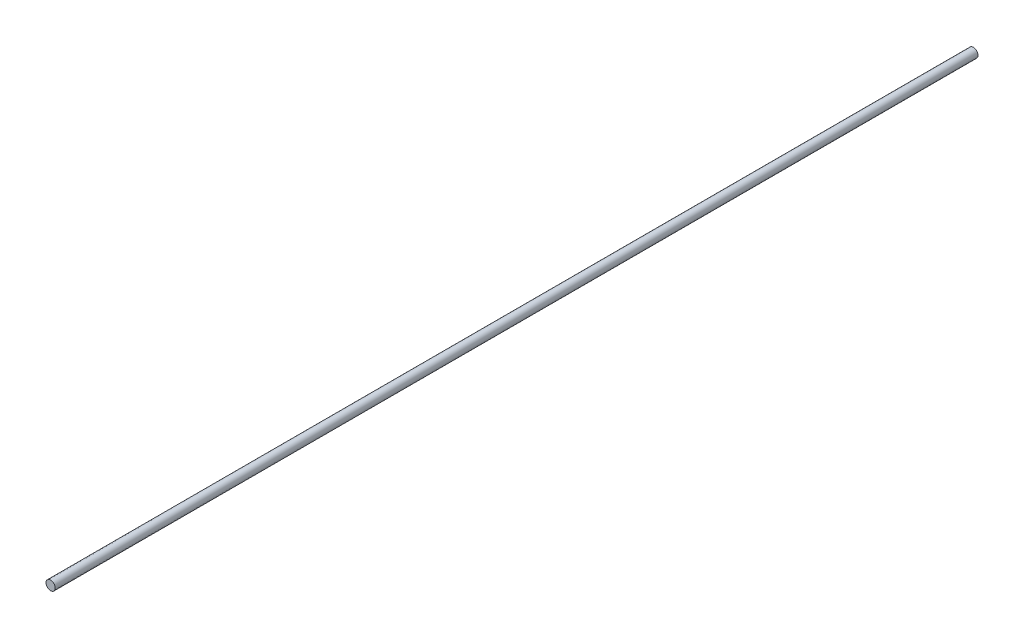
SolidWorks part; units mm, degrees
ref_plane "Front Plane" through (0, 0, 0) normal (0, 0, 1) x (1, 0, 0)
ref_plane "Top Plane" through (0, 0, 0) normal (0, 1, 0) x (1, 0, 0)
ref_plane "Right Plane" through (0, 0, 0) normal (1, 0, 0) x (0, 0, -1)
sketch "Sketch1" plane through (0, 0, 0) normal (0, 0, 1) x (1, 0, 0)
  circle A0 centre (0, 0) radius 0.5
extrude "Boss-Extrude1" add sketch "Sketch1" along normal blind 100
